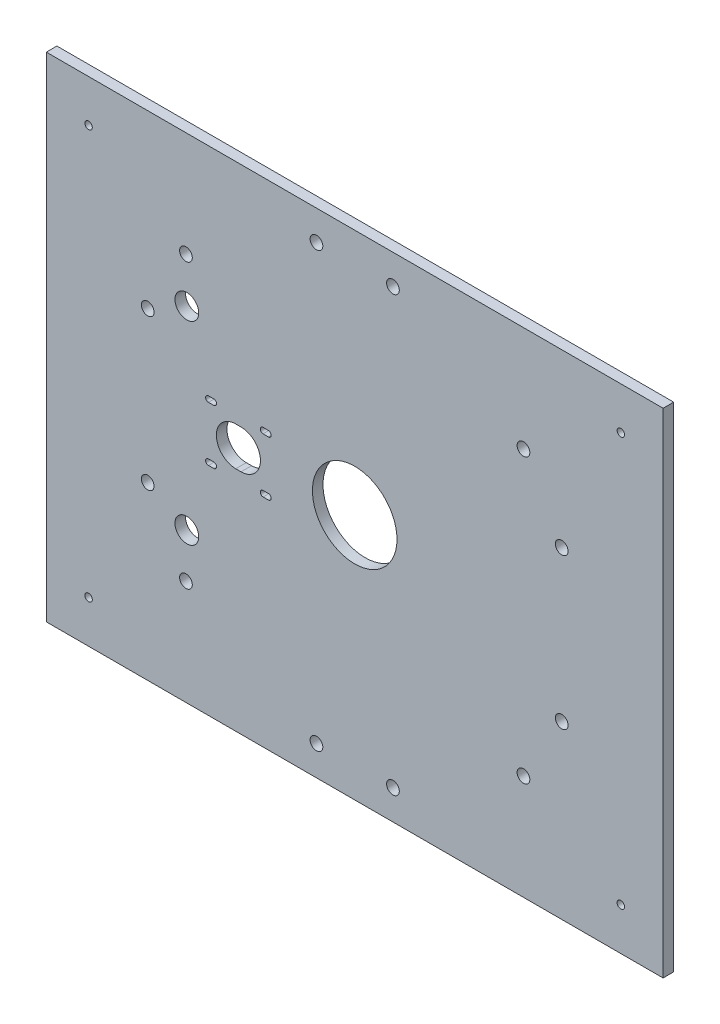
SolidWorks part; units mm, degrees
material "Acrílico (médio-alto impacto)"
ref_plane "Front Plane" through (0, 0, 0) normal (0, 0, 1) x (1, 0, 0)
ref_plane "Top Plane" through (0, 0, 0) normal (0, 1, 0) x (1, 0, 0)
ref_plane "Right Plane" through (0, 0, 0) normal (1, 0, 0) x (0, 0, -1)
ref_plane "Plano1" through (0, 0, 5) normal (0, 0, 1) x (1, 0, 0)
sketch "Esboço1" plane through (0, 0, 5) normal (0, 0, 1) x (1, 0, 0)
  line L1 (-175, -140) -> (175, -140)
  line L2 (-175, -140) -> (-175, 140)
  line L3 (-175, 140) -> (175, 140)
  line L4 (175, -140) -> (175, 140)
  line L5 (-175, -140) -> (175, 140) construction
  line L6 (-175, 140) -> (175, -140) construction
  point P0 (0, 0)
  dimension "D1" = 280
  dimension "D2" = 350
extrude "Ressalto-extrusão1" add sketch "Esboço1" against normal blind 6
sketch "Esboço2" plane through (0, 0, 5) normal (0, 0, 1) x (1, 0, 0)
  circle A0 centre (0, 0) radius 24
  dimension "D1" = 48
extrude "Corte-extrusão1" cut sketch "Esboço2" against normal through all
hole_wizard "Furos-guia com Ø8.0mm1" positions "Esboço3" profile "Esboço4" hole size "Ø8.0" standard "ISO" end condition through all
sketch "Esboço3" plane through (0, 0, 5) normal (0, 0, 1) x (1, 0, 0)
  line L5 (175, 140) -> (-175, 140) construction
  line L6 (-175, 140) -> (-175, -140) construction
  point P18 (-67.5, 0)
  dimension "D1" = 107.5
  dimension "D2" = 140
sketch "Esboço4" plane through (-67.5, 0, 5) normal (1, 0, 0) x (0, -1, 0)
  line L0 (0, 0) -> (0, 6)
  line L1 (0, 6) -> (4, 6)
  line L2 (4, 6) -> (4, 0)
  line L5 (4, 0) -> (0, 0)
  line L11 (0, -6.35) -> (0, 107.95) construction
  dimension "Thru Hole Dia." = 8
  dimension "Thru Hole Depth" = 6
hole_wizard "Furo de diâmetro Ø3.2 (3.2)1" positions "Esboço5" profile "Esboço6" hole size "Ø3.2" standard "ISO" end condition through all
sketch "Esboço5" plane through (0, 0, 5) normal (0, 0, 1) x (1, 0, 0)
  point P17 (-83, 15.5)
  point P21 (-83, -15.5)
  point P23 (-52, 15.5)
  point P24 (-52, -15.5)
  point P26 (-52, -15.5)
sketch "Esboço6" plane through (-83, 15.5, 5) normal (1, 0, 0) x (0, -1, 0)
  line L0 (0, 0) -> (0, 6)
  line L1 (0, 6) -> (1.6, 6)
  line L2 (1.6, 6) -> (1.6, 0)
  line L5 (1.6, 0) -> (0, 0)
  line L11 (0, -6.35) -> (0, 107.95) construction
  dimension "Thru Hole Dia." = 3.2
  dimension "Thru Hole Depth" = 6
hole_wizard "Furo com folga de M121" positions "Esboço7" profile "Esboço8" hole size "M12" standard "ISO" end condition through all
sketch "Esboço7" plane through (0, 0, 5) normal (0, 0, 1) x (1, 0, 0)
  line L0 (-135, -135) -> (-105, -135) construction
  line L1 (-135, 135) -> (-135, 105) construction
  point P0 (-95.2628, 55)
  point P3 (-95.2628, -55)
  dimension "D1" = 110
  dimension "D2" = 80
  dimension "D3" = 39.7372
sketch "Esboço8" plane through (-95.2628, 55, 5) normal (1, 0, 0) x (0, -1, 0)
  line L0 (0, 0) -> (0, 6)
  line L1 (0, 6) -> (6.75, 6)
  line L2 (6.75, 6) -> (6.75, 0)
  line L5 (6.75, 0) -> (0, 0)
  line L11 (0, -6.35) -> (0, 107.95) construction
  dimension "Thru Hole Dia." = 13.5
  dimension "Thru Hole Depth" = 6
sketch "Esboço9" plane through (0, 0, 5) normal (0, 0, 1) x (1, 0, 0)
  line L0 (-95.2628, 55) -> (108.2532, -62.5) construction
  line L1 (-95.7556, 80.3485) -> (0, 0) construction
  line L2 (0, 125) -> (0, -125) construction
  circle A0 centre (0, 0) radius 125 construction
  circle A1 centre (-95.7556, 80.3485) radius 3.6
  circle A2 centre (-117.4616, 42.7525) radius 3.6
  circle A3 centre (21.706, 123.101) radius 3.6
  circle A4 centre (-21.706, 123.101) radius 3.6
  circle A5 centre (117.4616, 42.7525) radius 3.6
  circle A6 centre (95.7556, 80.3485) radius 3.6
  circle A7 centre (95.7556, -80.3485) radius 3.6
  circle A8 centre (117.4616, -42.7525) radius 3.6
  circle A9 centre (-21.706, -123.101) radius 3.6
  circle A10 centre (21.706, -123.101) radius 3.6
  circle A11 centre (-117.4616, -42.7525) radius 3.6
  circle A12 centre (-95.7556, -80.3485) radius 3.6
  point P34 (0, 0)
  dimension "D1" = 250
  dimension "D2" = 7.2
  dimension "D3" = 10
  dimension "D4" = 6
extrude "Corte-extrusão2" cut sketch "Esboço9" against normal blind 10
hole_wizard "Furo de diâmetro Ø4.2 (4.2)1" positions "Esboço10" profile "Esboço11" hole size "Ø4.2" standard "ISO" end condition through all
sketch "Esboço10" plane through (0, 0, 5) normal (0, 0, 1) x (1, 0, 0)
  point P19 (-151, 116)
  point P22 (151, 116)
  point P24 (151, -116)
  point P26 (-151, -116)
sketch "Esboço11" plane through (-151, 116, 5) normal (1, 0, 0) x (0, -1, 0)
  line L0 (0, 0) -> (0, 6)
  line L1 (0, 6) -> (2.1, 6)
  line L2 (2.1, 6) -> (2.1, 0)
  line L5 (2.1, 0) -> (0, 0)
  line L11 (0, -6.35) -> (0, 107.95) construction
  dimension "Thru Hole Dia." = 4.2
  dimension "Thru Hole Depth" = 6
sketch "Esboço12" plane through (0, 0, 5) normal (0, 0, 1) x (1, 0, 0)
  line L0 (-67.5, 0) -> (-64.5, 0) construction
  line L3 (-67.5, 11) -> (-64.5, 11)
  line L4 (-67.5, -11) -> (-64.5, -11)
  line L5 (-83, 15.5) -> (-80, 15.5) construction
  line L6 (-83, 17.1) -> (-80, 17.1)
  line L7 (-83, 13.9) -> (-80, 13.9)
  line L8 (-83, -15.5) -> (-80, -15.5) construction
  line L9 (-83, -13.9) -> (-80, -13.9)
  line L10 (-83, -17.1) -> (-80, -17.1)
  line L11 (-52, 15.5) -> (-49, 15.5) construction
  line L12 (-52, 17.1) -> (-49, 17.1)
  line L13 (-52, 13.9) -> (-49, 13.9)
  line L14 (-52, -15.5) -> (-49, -15.5) construction
  line L15 (-52, -13.9) -> (-49, -13.9)
  line L16 (-52, -17.1) -> (-49, -17.1)
  arc A2 (-67.5, 11) -> (-67.5, -11) centre (-67.5, 0) ccw
  arc A3 (-64.5, -11) -> (-64.5, 11) centre (-64.5, 0) ccw
  arc A4 (-83, 17.1) -> (-83, 13.9) centre (-83, 15.5) ccw
  arc A5 (-80, 13.9) -> (-80, 17.1) centre (-80, 15.5) ccw
  arc A6 (-83, -13.9) -> (-83, -17.1) centre (-83, -15.5) ccw
  arc A7 (-80, -17.1) -> (-80, -13.9) centre (-80, -15.5) ccw
  arc A8 (-52, 17.1) -> (-52, 13.9) centre (-52, 15.5) ccw
  arc A9 (-49, 13.9) -> (-49, 17.1) centre (-49, 15.5) ccw
  arc A10 (-52, -13.9) -> (-52, -17.1) centre (-52, -15.5) ccw
  arc A11 (-49, -17.1) -> (-49, -13.9) centre (-49, -15.5) ccw
  circle A12 centre (-83, 15.5) radius 1.6 construction
  point P2 (-66, 0)
  point P14 (-81.5, 15.5)
  point P19 (-81.5, -15.5)
  point P27 (-50.5, 15.5)
  point P35 (-50.5, -15.5)
  dimension "D2" = 11
  dimension "D1" = 3
  dimension "D3" = 3
extrude "Corte-extrusão3" cut sketch "Esboço12" against normal through all
